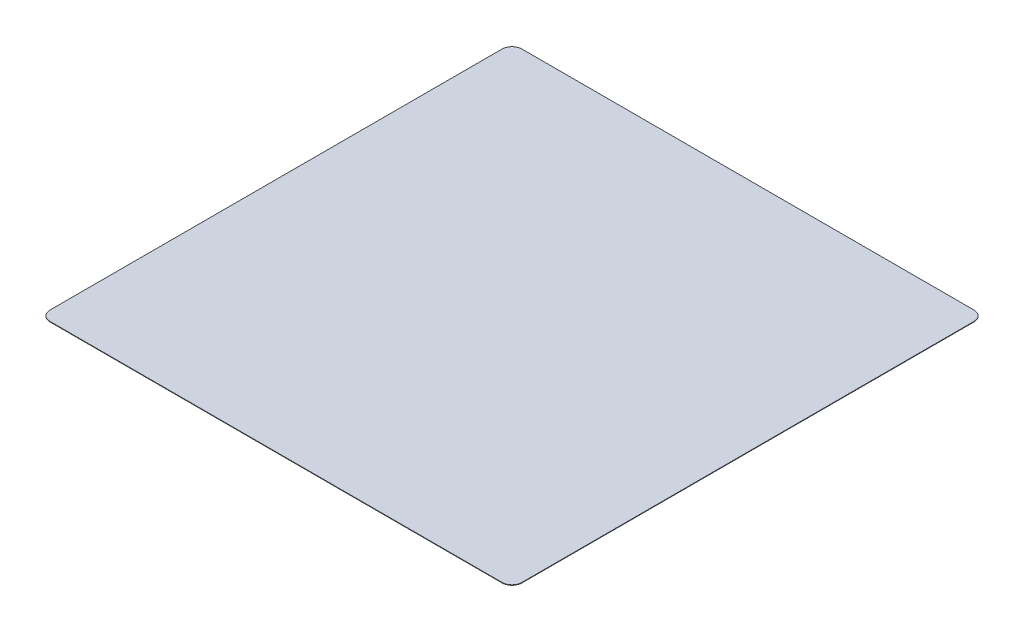
SolidWorks part; units mm, degrees
ref_plane "Front Plane" through (0, 0, 0) normal (0, 0, 1) x (1, 0, 0)
ref_plane "Top Plane" through (0, 0, 0) normal (0, 1, 0) x (1, 0, 0)
ref_plane "Right Plane" through (0, 0, 0) normal (1, 0, 0) x (0, 0, -1)
sketch "Sketch1" plane through (0, 0, 0) normal (0, 1, 0) x (1, 0, 0)
  line L1 (-47.35, -47.35) -> (47.35, -47.35)
  line L2 (-47.35, -47.35) -> (-47.35, 47.35)
  line L3 (-47.35, 47.35) -> (47.35, 47.35)
  line L4 (47.35, -47.35) -> (47.35, 47.35)
  line L5 (-47.35, -47.35) -> (47.35, 47.35) construction
  line L6 (-47.35, 47.35) -> (47.35, -47.35) construction
  point P0 (0, 0)
  dimension "D1" = 94.7
  dimension "D2" = 94.7
extrude "Boss-Extrude1" add sketch "Sketch1" along normal blind 0.1
fillet "Fillet1" radius 2 4 edges at (-47.35, 0.05, -47.35) (47.35, 0.05, -47.35) (47.35, 0.05, 47.35) (-47.35, 0.05, 47.35)
